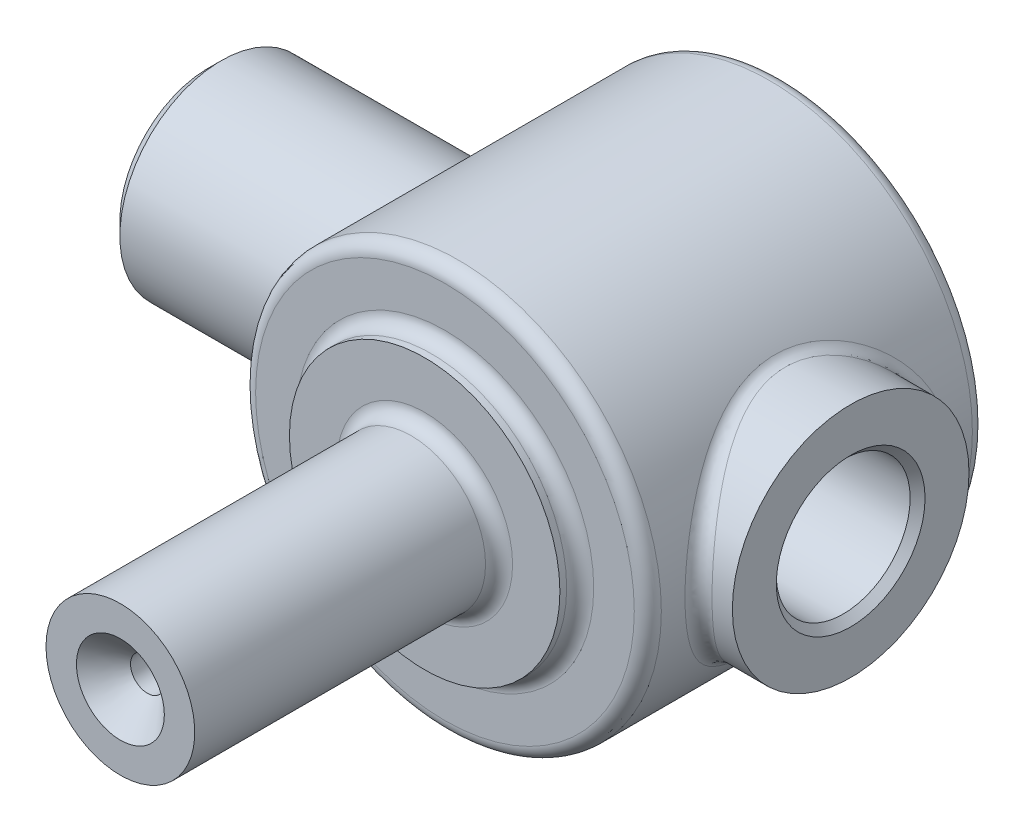
SolidWorks part; units mm, degrees
material "Сталь 08Х17Т ГОСТ 5632-72"
ref_plane "Спереди" through (0, 0, 0) normal (0, 0, 1) x (1, 0, 0)
ref_plane "Сверху" through (0, 0, 0) normal (0, 1, 0) x (1, 0, 0)
ref_plane "Справа" through (0, 0, 0) normal (1, 0, 0) x (0, 0, -1)
sketch "Эскиз1" plane through (0, 0, 0) normal (0, 0, 1) x (1, 0, 0)
  circle A0 centre (0, 0) radius 30
  dimension "D1" = 60
extrude "Бобышка-Вытянуть1" add sketch "Эскиз1" along normal blind 50
sketch "Эскиз2" plane through (0, 0, 50) normal (0, 0, 1) x (1, 0, 0)
  circle A0 centre (0, 0) radius 20
  dimension "D1" = 40
extrude "Бобышка-Вытянуть2" add sketch "Эскиз2" along normal blind 3
sketch "Эскиз3" plane through (0, 0, 53) normal (0, 0, 1) x (1, 0, 0)
  circle A0 centre (0, 0) radius 11
  dimension "D1" = 22
extrude "Бобышка-Вытянуть3" add sketch "Эскиз3" along normal blind 45
sketch "Эскиз4" plane through (0, 0, 0) normal (1, 0, 0) x (0, 0, -1)
  line L0 (0, 0) -> (-50, 0) construction
  line L1 (0, -30) -> (0, 30) construction
  line L2 (-50, 30) -> (-50, -30) construction
  circle A0 centre (-25, 0) radius 17.5
  dimension "D1" = 35
extrude "Бобышка-Вытянуть4" add sketch "Эскиз4" along normal blind 35 and the other way blind 10
sketch "Эскиз8" plane through (0, 0, 0) normal (1, 0, 0) x (0, 0, -1)
  line L0 (0, 0) -> (-50, 0) construction
  line L1 (-50, 30) -> (-50, -30) construction
  circle A0 centre (-25, 0) radius 15
  dimension "D1" = 30
extrude "Бобышка-Вытянуть5" add sketch "Эскиз8" against normal blind 60
cosmetic thread "Условное изображение резьбы2" parameters "D1"=30, "D2"=26.158
sketch "Эскиз5" plane through (0, 0, 0) normal (0, 1, 0) x (1, 0, 0)
  line L0 (-60, -25) -> (35, -25) construction
  line L2 (35, -42.5) -> (35, -7.5) construction
  line L3 (35, -25) -> (35, -34.5)
  line L4 (35, -34.5) -> (-15, -34.5)
  line L5 (-15, -34.5) -> (-15, -32.172)
  line L6 (-15, -32.172) -> (-40, -32.172)
  line L7 (-40, -32.172) -> (-40, -36)
  line L8 (-40, -36) -> (-60, -36)
  line L9 (-60, -36) -> (-60, -25)
  line L10 (-60, -25) -> (35, -25)
  line L11 (-60, -10) -> (-60, -40) construction
  dimension "D1" = 19
  dimension "D2" = 50
  dimension "D3" = 14.344
  dimension "D4" = 25
  dimension "D5" = 22
revolve "Вырез-Повернуть1" cut sketch "Эскиз5" angle 360 about L0
cosmetic thread "Условное изображение резьбы3" parameters "D2"=16
sketch "Эскиз6" plane through (0, 0, 0) normal (0, 1, 0) x (1, 0, 0)
  line L0 (0, -98) -> (0, 0) construction
  line L1 (-11, -98) -> (11, -98) construction
  line L2 (6.5, -98) -> (2.5, -94)
  line L3 (2.5, -94) -> (2.5, -30)
  line L4 (35, -25) -> (-60, -25) construction
  line L5 (35, -34.5) -> (35, -15.5) construction
  line L7 (2.5, -30) -> (0, -30)
  line L8 (6.5, -98) -> (0, -98)
  line L9 (0, -98) -> (0, -30)
  line L10 (-60, -10) -> (-60, -40) construction
  dimension "D1" = 5
  dimension "D2" = 4
  dimension "D3" = 45
  dimension "D4" = 5
revolve "Вырез-Повернуть2" cut sketch "Эскиз6" angle 360 about L9
fillet "Скругление1" radius 2 6 edges at (20, 0, 50) (30, 0, 50) (30, 0, 0) (29.585, 4.9728, 41.7786) (11, 0, 53) (-29.9618, 1.5136, 10.0766)
sketch "Эскиз7" plane through (35, 0, 0) normal (1, 0, 0) x (0, 0, -1)
  circle A0 centre (-25, 0) radius 9.8985
  dimension "D1" = 19.797
extrude "Вырез-Вытянуть1" cut sketch "Эскиз7" against normal up to surface (50 mm away) up to face at (-15, 0, 34.5)
cosmetic thread "Условное изображение резьбы1" parameters "D1"=5, "D2"=22
chamfer "Фаска1" distance 1.1015 angle 45 1 edges at (35, 0, 15.1015)
chamfer "Фаска2" distance 1.921 angle 45 1 edges at (-60, 0, 10)
chamfer "Фаска3" distance 0.828 angle 45 1 edges at (-40, 0, 32.172)
